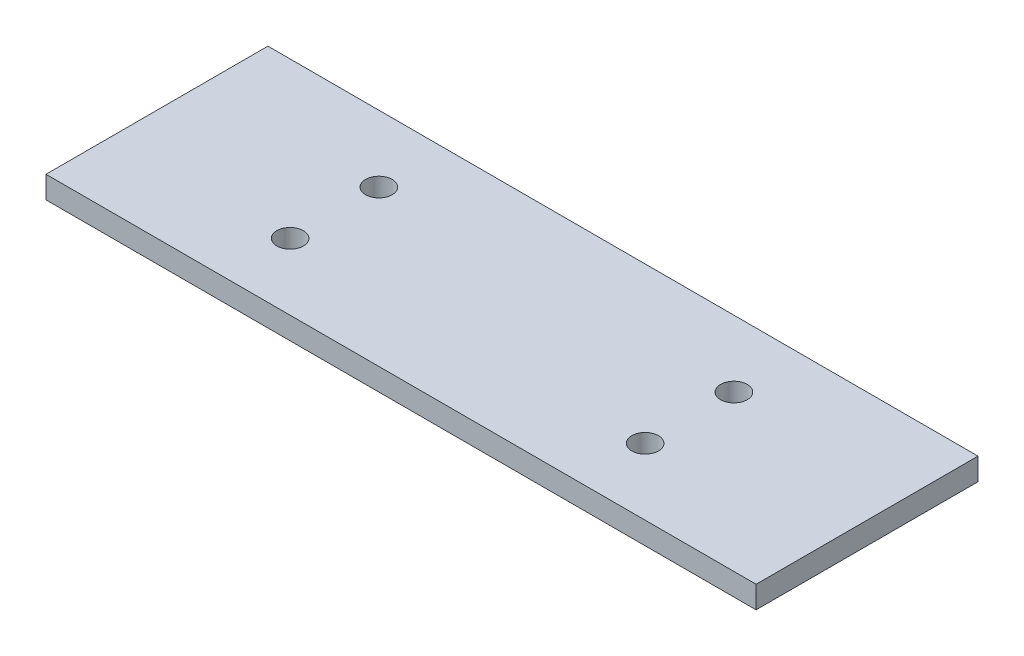
SolidWorks part; units mm, degrees
ref_plane "Ebene vorne" through (0, 0, 0) normal (0, 0, 1) x (1, 0, 0)
ref_plane "Ebene oben" through (0, 0, 0) normal (0, 1, 0) x (1, 0, 0)
ref_plane "Ebene rechts" through (0, 0, 0) normal (1, 0, 0) x (0, 0, -1)
sketch "Skizze1" plane through (0, 0, 0) normal (0, 1, 0) x (1, 0, 0)
  line L1 (-80, -25) -> (80, -25)
  line L2 (-80, -25) -> (-80, 25)
  line L3 (-80, 25) -> (80, 25)
  line L4 (80, -25) -> (80, 25)
  line L5 (-80, -25) -> (80, 25) construction
  line L6 (-80, 25) -> (80, -25) construction
  circle A0 centre (-40, 10) radius 3
  circle A1 centre (-40, -10) radius 3
  circle A2 centre (40, 10) radius 3
  circle A3 centre (40, -10) radius 3
  point P0 (0, 0)
  point P16 (0, 0)
  dimension "D3" = 6
  dimension "D4" = 6
  dimension "D5" = 6
  dimension "D6" = 6
  dimension "D1" = 160
  dimension "D2" = 50
  dimension "D7" = 80
  dimension "D8" = 40
  dimension "D9" = 40
  dimension "D10" = 80
  dimension "D11" = 40
  dimension "D12" = 15
  dimension "D13" = 15
  dimension "D14" = 20
  dimension "D15" = 15
extrude "Aufsatz-Linear austragen1" add sketch "Skizze1" along normal blind 5
